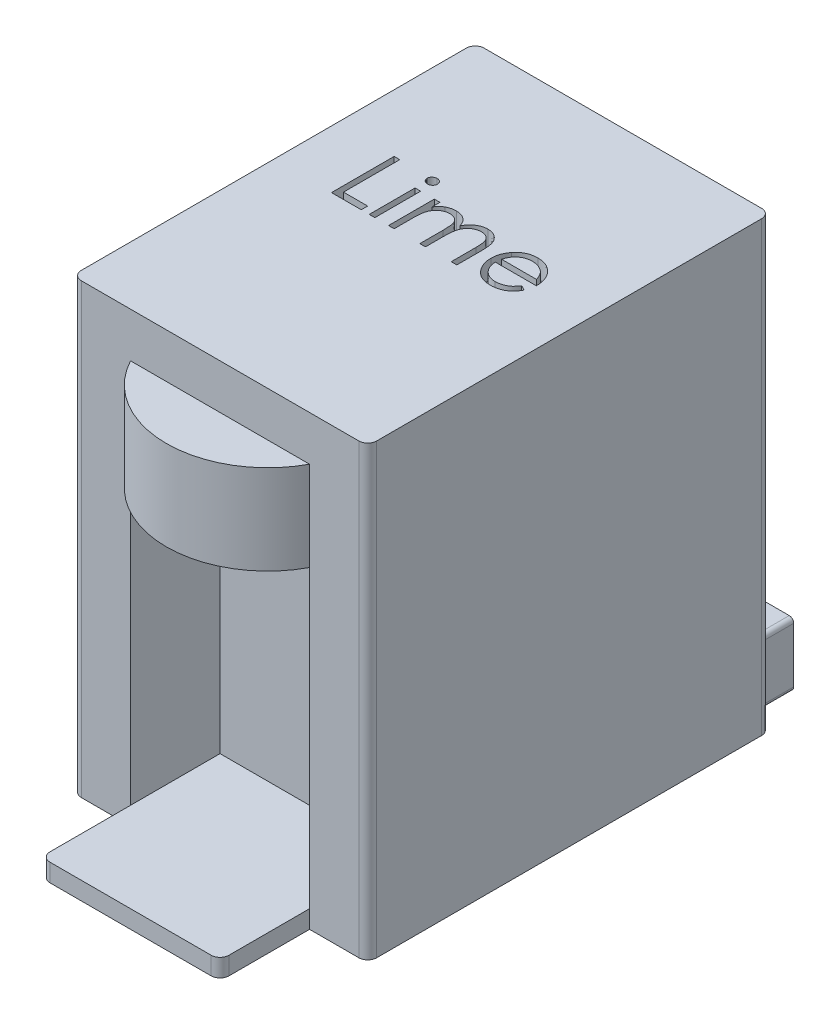
SolidWorks part; units mm, degrees
ref_plane "Front Plane" through (0, 0, 0) normal (0, 0, 1) x (1, 0, 0)
ref_plane "Top Plane" through (0, 0, 0) normal (0, 1, 0) x (1, 0, 0)
ref_plane "Right Plane" through (0, 0, 0) normal (1, 0, 0) x (0, 0, -1)
sketch "Sketch1" plane through (0, 0, 0) normal (0, 1, 0) x (1, 0, 0)
  line L1 (-165, -225) -> (165, -225)
  line L2 (-165, -225) -> (-165, 225)
  line L3 (-165, 225) -> (165, 225)
  line L4 (165, -225) -> (165, 225)
  line L5 (-165, -225) -> (165, 225) construction
  line L6 (-165, 225) -> (165, -225) construction
  point P0 (0, 0)
  dimension "D1" = 330
  dimension "D2" = 450
extrude "Boss-Extrude1" add sketch "Sketch1" along normal blind 500
sketch "Sketch2" plane through (0, 0, 225) normal (0, 0, 1) x (1, 0, 0)
  line L0 (-165, 0) -> (165, 0) construction
  line L1 (-100, 0) -> (100, 0)
  line L2 (-100, 0) -> (-100, 350)
  line L3 (-100, 350) -> (100, 350)
  line L4 (100, 0) -> (100, 350)
  point P6 (0, 0)
  dimension "D1" = 200
  dimension "D2" = 350
extrude "Cut-Extrude1" cut sketch "Sketch2" against normal blind 100
sketch "Sketch3" plane through (0, 350, 0) normal (0, -1, 0) x (1, 0, 0)
  line L0 (100, 225) -> (-100, 225) construction
  line L1 (100, 225) -> (-100, 225)
  arc A0 (-100, 225) -> (100, 225) centre (0, 171.6242) cw
extrude "Boss-Extrude2" add sketch "Sketch3" against normal blind 100
sketch "Sketch4" plane through (0, 0, 125) normal (0, 0, 1) x (1, 0, 0)
  line L0 (100, 0) -> (100, 350) construction
  line L1 (-100, 0) -> (100, 0)
  line L2 (-100, 0) -> (-100, 20)
  line L3 (-100, 20) -> (100, 20)
  line L4 (100, 0) -> (100, 20)
  dimension "D1" = 20
extrude "Boss-Extrude3" add sketch "Sketch4" along normal blind 200
sketch "Sketch5" plane through (0, 350, 0) normal (0, -1, 0) x (1, 0, 0)
  circle A0 centre (0, 203.1713) radius 58.985
extrude "Cut-Extrude2" cut sketch "Sketch5" against normal blind 50
fillet "Fillet1" radius 10 4 edges at (165, 250, 225) (-165, 250, 225) (-165, 250, -225) (165, 250, -225)
sketch "Sketch6" plane through (0, 0, -225) normal (0, 0, -1) x (-1, 0, 0)
  line L0 (-155, 0) -> (155, 0) construction
  line L1 (-140.8441, 0) -> (-32.0502, 0)
  line L2 (-140.8441, 0) -> (-140.8441, 71.4886)
  line L3 (-140.8441, 71.4886) -> (-32.0502, 71.4886)
  line L4 (-32.0502, 0) -> (-32.0502, 71.4886)
extrude "Boss-Extrude4" add sketch "Sketch6" along normal blind 50
fillet "Fillet2" radius 5 4 edges at (140.8441, 0, -250) (140.8441, 71.4886, -250) (32.0502, 0, -250) (32.0502, 71.4886, -250)
fillet "Fillet3" radius 10 2 edges at (-100, 10, 325) (100, 10, 325)
sketch "Sketch7" plane through (0, 500, 0) normal (0, 1, 0) x (1, 0, 0)
  line L0 (-165, 0) -> (165, 0) construction
  line L1 (-165, 215) -> (-165, -215) construction
  line L2 (165, -215) -> (165, 215) construction
  text T0 "Lime" font "Century Gothic" height 70
extrude "Cut-Extrude3" cut sketch "Sketch7" against normal blind 20
